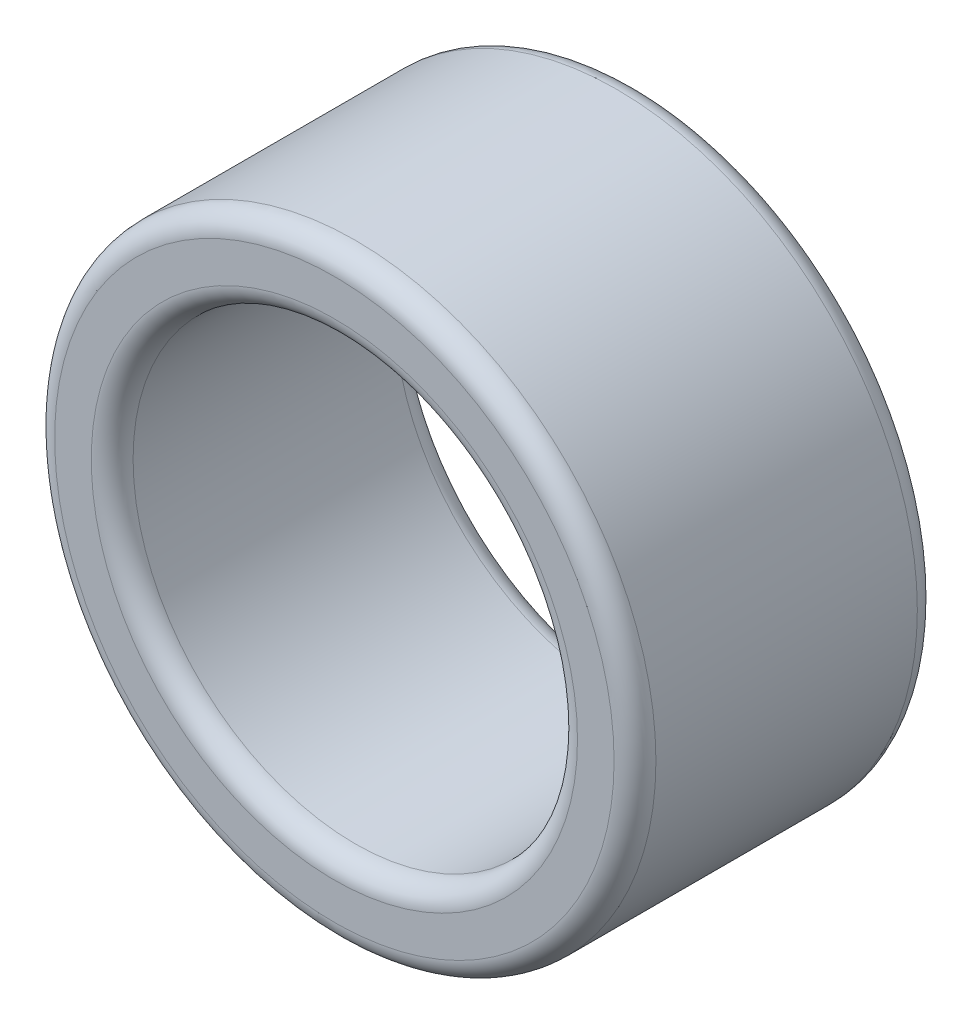
SolidWorks part; units mm, degrees
ref_plane "Спереди" through (0, 0, 0) normal (0, 0, 1) x (1, 0, 0)
ref_plane "Сверху" through (0, 0, 0) normal (0, 1, 0) x (1, 0, 0)
ref_plane "Справа" through (0, 0, 0) normal (1, 0, 0) x (0, 0, -1)
sketch "Эскиз1" plane through (0, 0, 0) normal (0, 0, 1) x (1, 0, 0)
  circle A0 centre (0, 0) radius 42.5
  circle A1 centre (0, 0) radius 57.5
  dimension "D1" = 115
  dimension "D2" = 85
extrude "тело" add sketch "Эскиз1" along normal mid plane 58
fillet "Скругление1" radius 4 4 edges at (42.5, 0, 29) (57.5, 0, 29) (42.5, 0, -29) (57.5, 0, -29)
